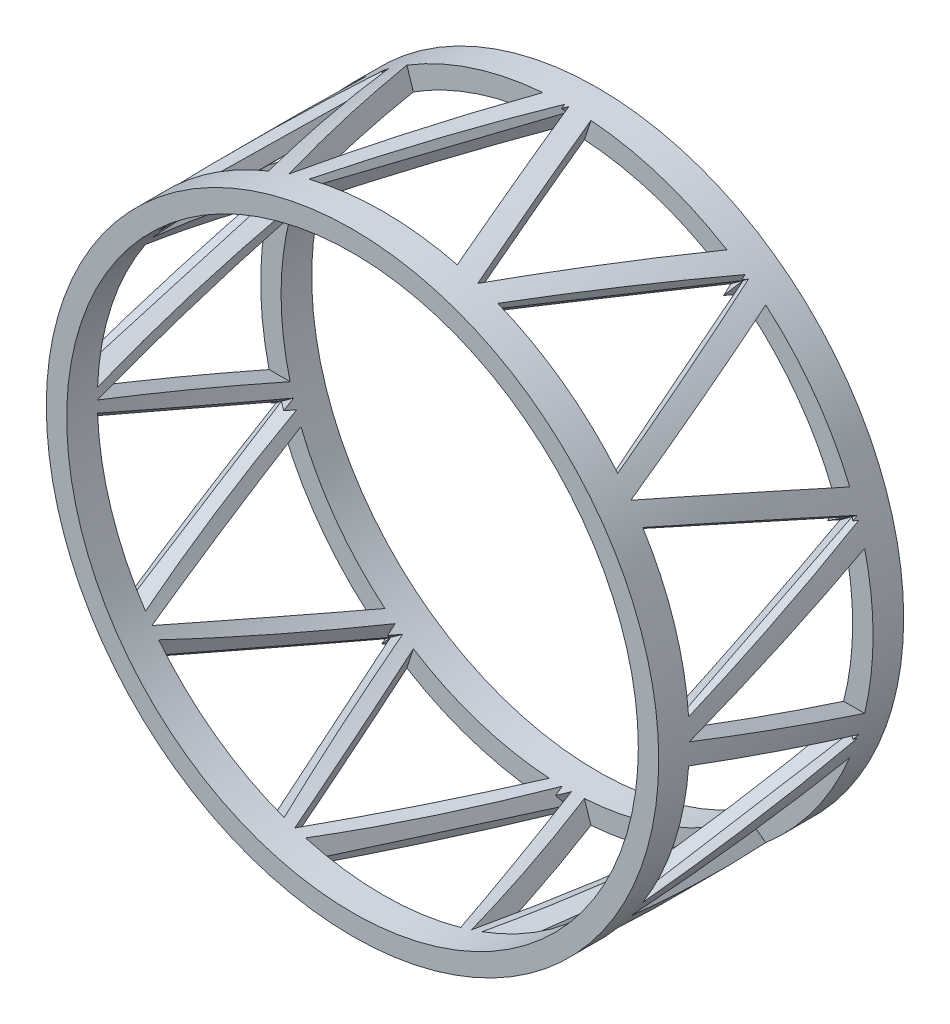
SolidWorks part; units mm, degrees
ref_plane "Front Plane" through (0, 0, 0) normal (0, 0, 1) x (1, 0, 0)
ref_plane "Top Plane" through (0, 0, 0) normal (0, 1, 0) x (1, 0, 0)
ref_plane "Right Plane" through (0, 0, 0) normal (1, 0, 0) x (0, 0, -1)
sketch "Sketch1" plane through (0, 0, 0) normal (0, 0, 1) x (1, 0, 0)
  circle A0 centre (0, 0) radius 15
  circle A1 centre (0, 0) radius 14
  dimension "D1" = 28
  dimension "D2" = 30
extrude "Boss-Extrude1" add sketch "Sketch1" along normal blind 12
sketch "Sketch2" plane through (0, 0, 0) normal (1, 0, 0) x (0, 0, -1)
  line L0 (0, 0) -> (-5.357, 0) construction
  line L1 (0, -15) -> (0, 15) construction
  line L2 (-1.5, 0) -> (-1.5, 3.5)
  line L4 (-10.5, 0) -> (-1.5, -3.5)
  line L5 (-1.5, -3.5) -> (-1.5, 0)
  line L6 (-12, 15) -> (-12, -15) construction
  line L7 (-10.5, 0) -> (-1.5, 3.5)
  dimension "D1" = 1.5
  dimension "D2" = 1.5
  dimension "D3" = 3.5
  dimension "D4" = 3.5
extrude "Cut-Extrude1" cut sketch "Sketch2" against normal mid plane 62
pattern_circular "CirPattern1" count 5 over 360 about axis through (0, 0, 0) along (0, 0, 1) of "Cut-Extrude1"
ref_plane "Plane1" through (-4.6353, 14.2658, 0) normal (-0.309, 0.9511, 0) x (0.9511, 0.309, 0)
sketch "Sketch7" plane through (-4.6353, 14.2658, 0) normal (-0.309, 0.9511, 0) x (0.9511, 0.309, 0)
  line L3 (-1.0418, -10.5) -> (-4.5418, -1.5)
  line L4 (0, -10.5) -> (-3.5, -1.5) construction
  line L7 (-1.0418, -10.5) -> (-7.7768, -10.5)
  line L8 (-4.5418, -1.5) -> (-7.7768, -10.5)
  dimension "D2" = 1.04
extrude "Cut-Extrude2" cut sketch "Sketch7" against normal blind 32
pattern_circular "CirPattern2" count 10 over 360 about axis through (0, 0, 0) along (0, 0, 1) of "Cut-Extrude2"
